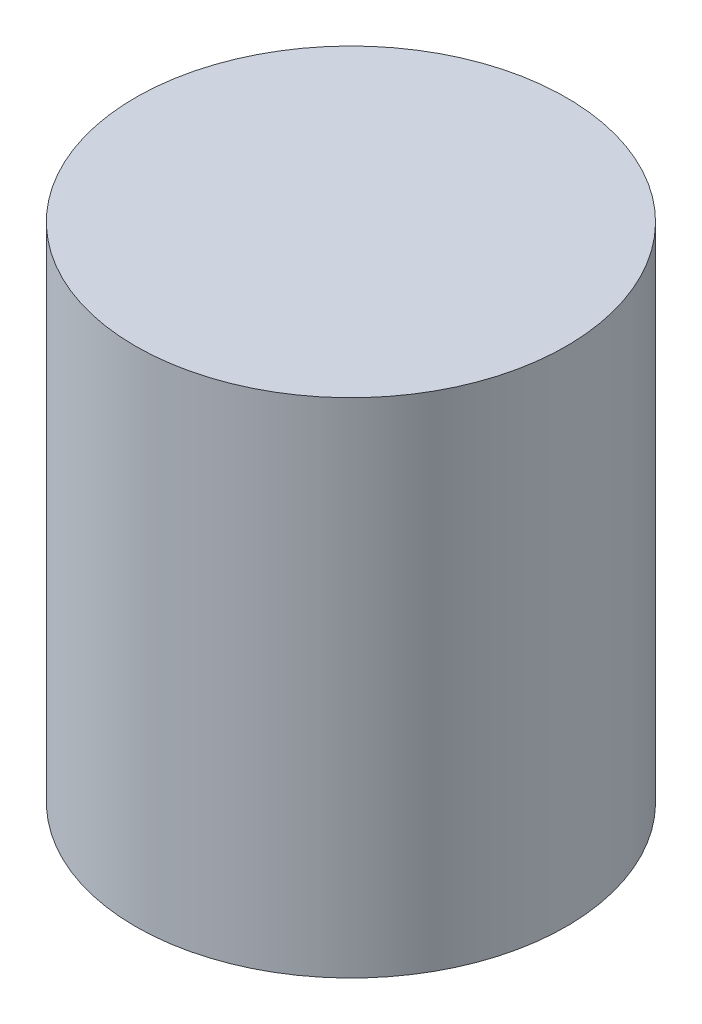
SolidWorks part; units mm, degrees
ref_plane "Front Plane" through (0, 0, 0) normal (0, 0, 1) x (1, 0, 0)
ref_plane "Top Plane" through (0, 0, 0) normal (0, 1, 0) x (1, 0, 0)
ref_plane "Right Plane" through (0, 0, 0) normal (1, 0, 0) x (0, 0, -1)
sketch "Sketch1" plane through (0, 0, 0) normal (0, 1, 0) x (1, 0, 0)
  circle A0 centre (0, 0) radius 3
  dimension "D1" = 6
extrude "Boss-Extrude1" add sketch "Sketch1" along normal blind 7
